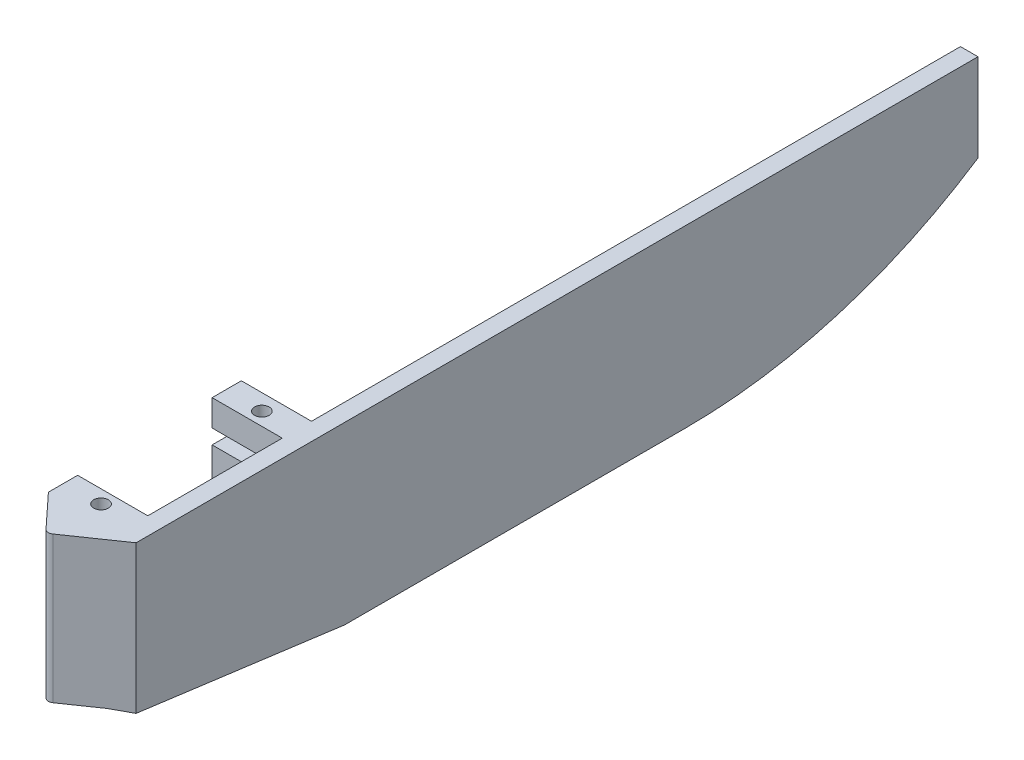
SolidWorks part; units mm, degrees
ref_plane "前视基准面" through (0, 0, 0) normal (0, 0, 1) x (1, 0, 0)
ref_plane "上视基准面" through (0, 0, 0) normal (0, 1, 0) x (1, 0, 0)
ref_plane "右视基准面" through (0, 0, 0) normal (1, 0, 0) x (0, 0, -1)
sketch "草图1" plane through (0, 0, 0) normal (1, 0, 0) x (0, 0, -1)
  line L1 (0, 0) -> (150, 0)
  line L2 (0, 0) -> (0, 30)
  line L3 (0, 30) -> (150, 30)
  line L4 (150, 0) -> (150, 30)
  dimension "D1" = 30
  dimension "D2" = 150
extrude "凸台-拉伸1" add sketch "草图1" along normal blind 3
sketch "草图2" plane through (3, 0, 0) normal (1, 0, 0) x (0, 0, -1)
  line L0 (150, 30) -> (0, 30) construction
  line L1 (6, 30) -> (11, 30)
  line L3 (6.0036, 25.5) -> (11, 25.5)
  line L4 (11, 30) -> (11, 25.5)
  line L5 (0, 30) -> (0, 0) construction
  line L6 (34, 30) -> (39, 30)
  line L7 (34, 30) -> (34, 25.5)
  line L8 (34, 25.5) -> (39, 25.5)
  line L9 (39, 30) -> (39, 25.5)
  line L10 (6.0036, 23) -> (11.0036, 23)
  line L12 (6.0036, 18) -> (11.0036, 18)
  line L13 (11.0036, 23) -> (11.0036, 18)
  line L14 (34.0036, 23) -> (39.0036, 23)
  line L15 (34.0036, 23) -> (34.0036, 18)
  line L16 (34.0036, 18) -> (39.0036, 18)
  line L17 (39.0036, 23) -> (39.0036, 18)
  line L18 (0, 0) -> (150, 0) construction
  line L19 (0, 30) -> (6, 30)
  line L20 (0, 30) -> (0, 0)
  line L21 (0, 0) -> (6.0036, 0)
  line L22 (6.0036, 25.5) -> (6.0036, 23)
  line L23 (6.0036, 18) -> (6.0036, 0)
  dimension "D1" = 4.5
  dimension "D2" = 4.5
  dimension "D3" = 5
  dimension "D4" = 5
  dimension "D5" = 2.5
  dimension "D6" = 23
  dimension "D7" = 5
  dimension "D8" = 23
  dimension "D9" = 5
  dimension "D10" = 5
  dimension "D11" = 5
  dimension "D12" = 11
  dimension "D13" = 6.0036
extrude "凸台-拉伸2" add sketch "草图2" along normal blind 12
sketch "草图3" plane through (0, 30, 0) normal (0, 1, 0) x (1, 0, 0)
  line L0 (15, 39) -> (15, 34) construction
  line L2 (15, 34) -> (3, 34) construction
  line L3 (15, 11) -> (3, 11) construction
  line L5 (15, 11) -> (15, 0) construction
  circle A0 centre (8.75, 36.25) radius 1.25
  circle A1 centre (8.75, 8.75) radius 1.25
  dimension "D1" = 2.5
  dimension "D2" = 2.5
  dimension "D3" = 6.25
  dimension "D4" = 2.25
  dimension "D5" = 2.25
  dimension "D6" = 6.25
extrude "切除-拉伸1" cut sketch "草图3" against normal blind 12
sketch "草图5" plane through (0, 30, 0) normal (0, 1, 0) x (1, 0, 0)
  line L0 (15, 11) -> (15, 0) construction
  line L1 (15, 0) -> (0, 0) construction
  line L2 (15, 6) -> (9.7333, 0.3201)
  line L3 (0, 6) -> (8.4317, 0.1771)
  line L4 (0, 150) -> (0, 0) construction
  line L5 (15, 11) -> (3, 11) construction
  line L6 (0, 6) -> (0, 0)
  line L7 (0, 0) -> (9, 0)
  line L8 (15, 6) -> (15, 0)
  line L9 (15, 0) -> (9, 0)
  arc A0 (9.7333, 0.3201) -> (8.4317, 0.1771) centre (9, 1) cw
  line M6 (0, 150) -> (0, 0)
  line M7 (0, 0) -> (15, 0)
  line M8 (15, 0) -> (15, 11)
  dimension "D1" = 6
  dimension "D4" = 1
  dimension "D2" = 5
  dimension "D3" = 5
extrude "切除-拉伸2" cut sketch "草图5" against normal blind 33 contours A0 L3 M7 M6 | L2 A0 M7 M8
sketch "草图6" plane through (0, 0, -6.0036) normal (0, 0, -1) x (-1, 0, 0)
  line L0 (-3, 0) -> (-3, 18) construction
  line L1 (-15, 0) -> (-3, 0)
  line L2 (-15, 0) -> (-15, 5)
  line L3 (-15, 5) -> (-3, 5)
  line L4 (-3, 0) -> (-3, 5)
  dimension "D1" = 5
extrude "切除-拉伸3" cut sketch "草图6" against normal blind 14
sketch "草图7" plane through (3, 0, 0) normal (1, 0, 0) x (0, 0, -1)
  line L1 (3.9282, 0) -> (150, 0) construction
  line L2 (41.6596, 0) -> (3.9282, 0)
  line L3 (3.9282, 0) -> (3.9282, 5)
  line L4 (3.9282, 5) -> (41.6596, 0)
extrude "切除-拉伸4" cut sketch "草图7" against normal blind 14
sketch "草图8" plane through (3, 0, 0) normal (1, 0, 0) x (0, 0, -1)
  line L0 (150, 0) -> (150, 30) construction
  line L1 (41.6596, 0) -> (150, 0) construction
  line L2 (100, 0) -> (150, 0)
  line L3 (150, 0) -> (150, 15)
  arc A0 (150, 15) -> (100, 0) centre (100, 90.8333) cw
  dimension "D1" = 15
  dimension "D2" = 50
extrude "切除-拉伸5" cut sketch "草图8" against normal blind 14
mirror "镜向2" about plane through (0, 0, 0) normal (1, 0, 0) of "凸台-拉伸1", "凸台-拉伸2", "切除-拉伸1", "切除-拉伸2", "切除-拉伸3", "切除-拉伸4", "切除-拉伸5"
sketch "草图9" plane through (0, 30, 0) normal (0, 1, 0) x (1, 0, 0)
  line L1 (0, 0) -> (52.5374, 0)
  line L2 (0, 0) -> (0, 169.0055)
  line L3 (0, 169.0055) -> (52.5374, 169.0055)
  line L4 (52.5374, 0) -> (52.5374, 169.0055)
extrude "切除-拉伸6" cut sketch "草图9" against normal blind 39
